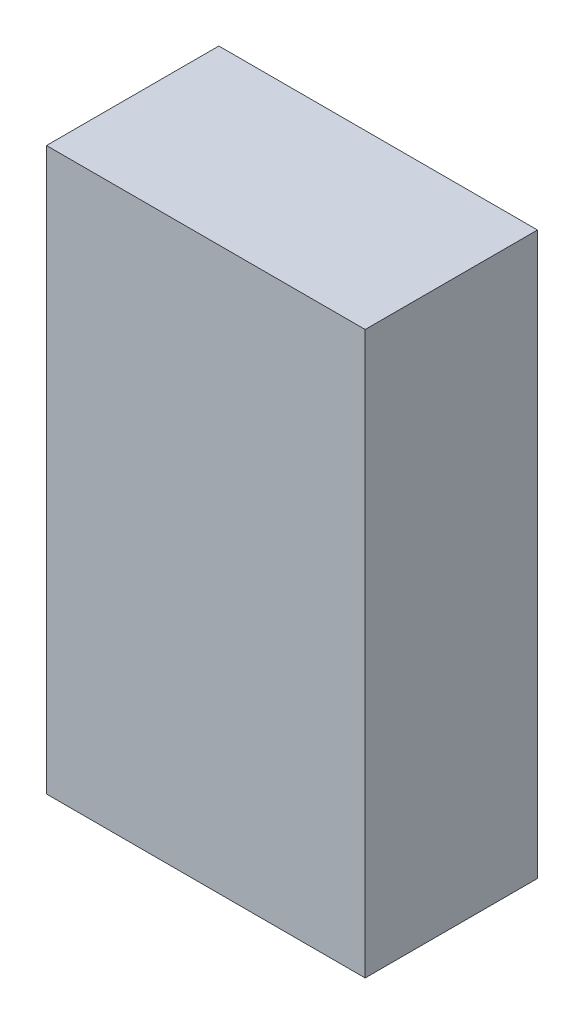
SolidWorks part; units mm, degrees
ref_plane "Front Plane" through (0, 0, 0) normal (0, 0, 1) x (1, 0, 0)
ref_plane "Top Plane" through (0, 0, 0) normal (0, 1, 0) x (1, 0, 0)
ref_plane "Right Plane" through (0, 0, 0) normal (1, 0, 0) x (0, 0, -1)
sketch "Sketch1" plane through (0, 0, 0) normal (0, 0, 1) x (1, 0, 0)
  line L1 (3, 52.5974) -> (-281.686, 52.5974)
  line L2 (3, 52.5974) -> (3, -449.1461)
  line L3 (3, -449.1461) -> (-281.686, -449.1461)
  line L4 (-281.686, 52.5974) -> (-281.686, -449.1461)
extrude "Boss-Extrude1" add sketch "Sketch1" against normal up to surface (153.9638 mm away)
